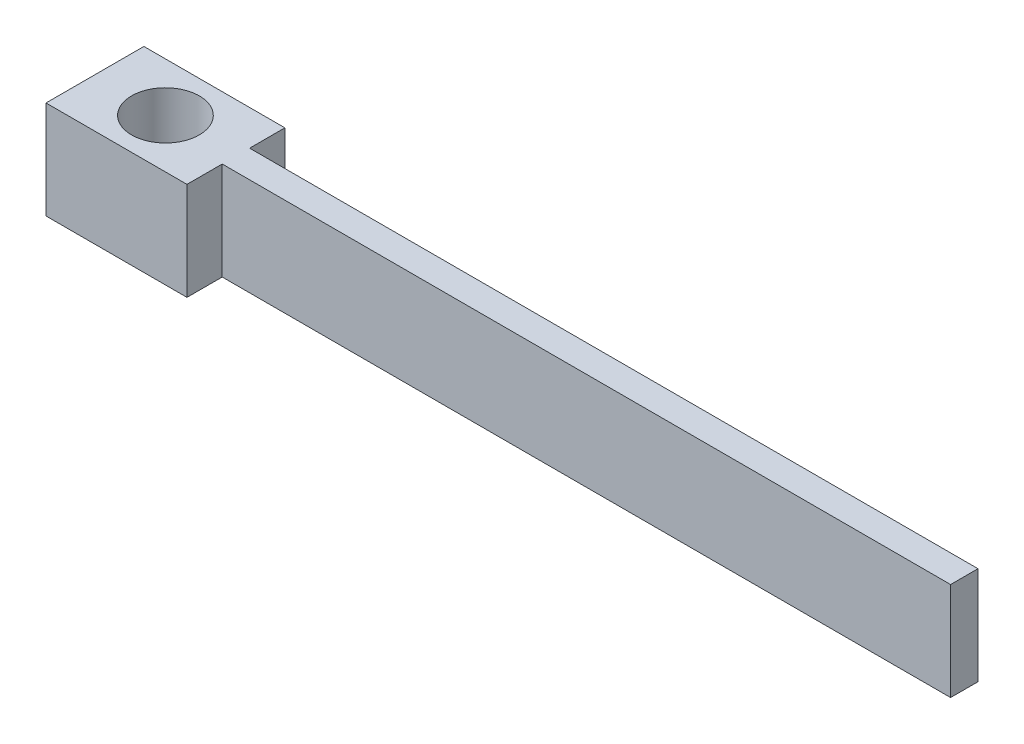
SolidWorks part; units mm, degrees
material "6061 Alloy"
ref_plane "Front Plane" through (0, 0, 0) normal (0, 0, 1) x (1, 0, 0)
ref_plane "Top Plane" through (0, 0, 0) normal (0, 1, 0) x (1, 0, 0)
ref_plane "Right Plane" through (0, 0, 0) normal (1, 0, 0) x (0, 0, -1)
sketch "Sketch1" plane through (0, 0, 0) normal (0, 1, 0) x (1, 0, 0)
  line L1 (-28.194, 3.175) -> (28.194, 3.175)
  line L2 (-28.194, 3.175) -> (-28.194, -3.175)
  line L3 (-28.194, -3.175) -> (28.194, -3.175)
  line L4 (28.194, 3.175) -> (28.194, -3.175)
  line L5 (-28.194, 3.175) -> (28.194, -3.175) construction
  line L6 (-28.194, -3.175) -> (28.194, 3.175) construction
  point P0 (0, 0)
  dimension "D1" = 6.35
  dimension "D2" = 56.388
extrude "Boss-Extrude1" add sketch "Sketch1" along normal mid plane 6.35
hole_wizard "#17 (0.173) Diameter Hole1" positions "Sketch2" profile "Sketch3" hole size "#17" standard "ANSI Inch" end condition up to next
sketch "Sketch2" plane through (0, 3.175, 0) normal (0, 1, 0) x (1, 0, 0)
  line L0 (-28.194, 3.175) -> (-28.194, -3.175) construction
  point P0 (-23.622, 0)
  dimension "D1" = 4.572
sketch "Sketch3" plane through (-23.622, 3.175, 0) normal (1, 0, 0) x (0, 0, 1)
  line L0 (0, 0) -> (0, 6.35)
  line L1 (0, 6.35) -> (2.1971, 6.35)
  line L2 (2.1971, 6.35) -> (2.1971, 0)
  line L5 (2.1971, 0) -> (0, 0)
  line L11 (0, -6.35) -> (0, 107.95) construction
  dimension "Thru Hole Dia." = 4.3942
  dimension "Thru Hole Depth" = 6.35
sketch "Sketch4" plane through (0, 3.175, 0) normal (0, 1, 0) x (1, 0, 0)
  line L0 (-28.194, 3.175) -> (-28.194, -3.175) construction
  line L1 (28.194, 3.175) -> (-19.05, 3.175)
  line L2 (28.194, 3.175) -> (28.194, 0.889)
  line L3 (28.194, 0.889) -> (-19.05, 0.889)
  line L4 (-19.05, 3.175) -> (-19.05, 0.889)
  dimension "D1" = 9.144
  dimension "D2" = 2.286
extrude "Cut-Extrude1" cut sketch "Sketch4" against normal through all
mirror "Mirror1" about plane through (0, 0, 0) normal (0, 0, 1) of "Cut-Extrude1"
